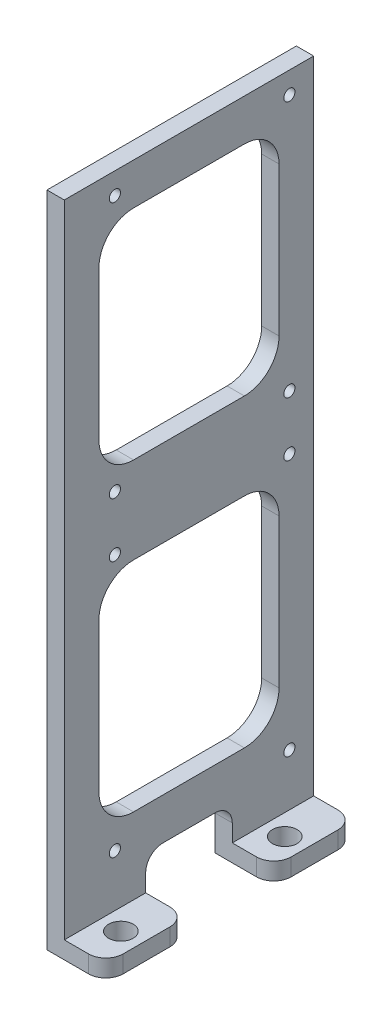
SolidWorks part; units mm, degrees
material "6061 Alloy"
ref_plane "Front Plane" through (0, 0, 0) normal (0, 0, 1) x (1, 0, 0)
ref_plane "Top Plane" through (0, 0, 0) normal (0, 1, 0) x (1, 0, 0)
ref_plane "Right Plane" through (0, 0, 0) normal (1, 0, 0) x (0, 0, -1)
sketch "Sketch1" plane through (0, 0, 0) normal (1, 0, 0) x (0, 0, -1)
  line L1 (-22.86, -60.325) -> (22.86, -60.325)
  line L2 (-22.86, -60.325) -> (-22.86, 60.325)
  line L3 (-22.86, 60.325) -> (22.86, 60.325)
  line L4 (22.86, -60.325) -> (22.86, 60.325)
  line L5 (-22.86, -60.325) -> (22.86, 60.325) construction
  line L6 (-22.86, 60.325) -> (22.86, -60.325) construction
  point P0 (0, 0)
  dimension "D1" = 120.65
  dimension "D2" = 45.72
extrude "Boss-Extrude1" add sketch "Sketch1" along normal blind 3.175
sketch "Sketch2" plane through (3.175, 0, 0) normal (1, 0, 0) x (0, 0, -1)
  line L0 (22.86, -60.325) -> (22.86, 60.325) construction
  line L1 (-22.86, -60.325) -> (22.86, -60.325)
  line L2 (-22.86, -60.325) -> (-22.86, -57.15)
  line L3 (-22.86, -57.15) -> (22.86, -57.15)
  line L4 (22.86, -60.325) -> (22.86, -57.15)
  dimension "D1" = 3.175
extrude "Boss-Extrude2" add sketch "Sketch2" along normal blind 7.62
sketch "Sketch3" plane through (0, -60.325, 0) normal (0, -1, 0) x (1, 0, 0)
  line L0 (10.795, 22.86) -> (10.795, -22.86) construction
  line L1 (0, -7.9375) -> (10.795, -7.9375)
  line L2 (0, -7.9375) -> (0, 7.9375)
  line L3 (0, 7.9375) -> (10.795, 7.9375)
  line L4 (10.795, -7.9375) -> (10.795, 7.9375)
  line L5 (0, -7.9375) -> (10.795, 7.9375) construction
  line L6 (0, 7.9375) -> (10.795, -7.9375) construction
  line L7 (0, 22.86) -> (0, -22.86) construction
  point P0 (5.3975, 0)
  dimension "D1" = 15.875
extrude "Cut-Extrude1" cut sketch "Sketch3" against normal blind 9.525
hole_wizard "M4 Clearance Hole1" positions "Sketch5" profile "Sketch4" hole size "M4" standard "Ansi Metric" end condition through all
sketch "Sketch5" plane through (0, -57.15, 0) normal (0, 1, 0) x (-1, 0, 0)
  line L7 (-6.985, 22.86) -> (-6.985, -22.86) construction
  line L8 (-10.795, 22.86) -> (-3.175, 22.86) construction
  line L9 (-10.795, -22.86) -> (-3.175, -22.86) construction
  line L11 (-22.011, 1.27) -> (-6.985, 16.296) construction
  line L13 (-22.011, 1.27) -> (-6.985, -13.756) construction
  circle A0 centre (-22.011, 1.27) radius 21.25
  point P0 (-6.985, -13.756)
  point P1 (-6.985, 16.296)
  dimension "D1" = 42.5
  dimension "D2" = 90
  dimension "D3" = 21.59
sketch "Sketch4" plane through (6.985, -57.15, -13.756) normal (1, 0, 0) x (0, 0, 1)
  line L0 (0, 0) -> (0, 3.175)
  line L1 (0, 3.175) -> (2.25, 3.175)
  line L2 (2.25, 3.175) -> (2.25, 0)
  line L5 (2.25, 0) -> (0, 0)
  line L11 (0, -6.35) -> (0, 107.95) construction
  dimension "Thru Hole Dia." = 4.5
  dimension "Thru Hole Depth" = 3.175
fillet "Fillet1" radius 3.175 2 edges at (1.5875, -50.8, 7.9375) (1.5875, -50.8, -7.9375)
fillet "Fillet2" radius 3.175 4 edges at (10.795, -58.7375, -22.86) (10.795, -58.7375, -7.9375) (10.795, -58.7375, 22.86) (10.795, -58.7375, 7.9375)
hole_wizard "M2.5x0.45 Tapped Hole1" positions "Sketch8" profile "Sketch9" tap size "M2.5x0.45" standard "Ansi Metric"
sketch "Sketch8" plane through (3.175, 0, 0) normal (1, 0, 0) x (0, 0, -1)
  line L1 (-13.585, 56.375) -> (18.415, 56.375) construction
  line L2 (-13.585, 56.375) -> (-13.585, -47.625) construction
  line L3 (-13.585, -47.625) -> (18.415, -47.625) construction
  line L4 (18.415, 56.375) -> (18.415, -47.625) construction
  line L5 (-13.585, 56.375) -> (18.415, -47.625) construction
  line L6 (-13.585, -47.625) -> (18.415, 56.375) construction
  line L7 (0, 60.325) -> (0, -50.8) construction
  line L8 (22.86, 60.325) -> (-22.86, 60.325) construction
  line L9 (-4.7625, -50.8) -> (4.7625, -50.8) construction
  line L10 (22.86, -57.15) -> (22.86, 60.325) construction
  point P174 (-13.585, -47.625)
  point P176 (18.415, -47.625)
  point P178 (18.415, -0.625)
  point P180 (-13.585, -0.625)
  point P182 (-13.585, 9.375)
  point P184 (18.415, 9.375)
  point P186 (18.415, 56.375)
  point P188 (-13.585, 56.375)
  dimension "D1" = 32
  dimension "D2" = 47
  dimension "D3" = 10
  dimension "D4" = 47
  dimension "D5" = 3.175
  dimension "D6" = 4.445
sketch "Sketch9" plane through (3.175, -47.625, 13.585) normal (0, 1, 0) x (0, 0, -1)
  line L0 (0, 0) -> (0, 6.9659)
  line L1 (0, 6.9659) -> (1.025, 6.35)
  line L2 (1.025, 6.35) -> (1.025, 0)
  line L5 (1.025, 0) -> (0, 0)
  line L10 (0, 6.9659) -> (-1.025, 6.35) construction
  line L11 (0, -6.35) -> (0, 107.95) construction
  dimension "Tap Drill Dia." = 2.05
  dimension "Tap Drill Depth" = 6.35
  dimension "Drill Angle" = 118
sketch "Sketch10" plane through (3.175, 0, 0) normal (1, 0, 0) x (0, 0, -1)
  line L0 (-22.86, 60.325) -> (-22.86, -57.15) construction
  line L1 (-16.51, 52.705) -> (16.51, 52.705)
  line L2 (-16.51, 52.705) -> (-16.51, 12.7)
  line L3 (-16.51, 12.7) -> (16.51, 12.7)
  line L4 (16.51, 52.705) -> (16.51, 12.7)
  line L5 (-16.51, 52.705) -> (16.51, 12.7) construction
  line L6 (-16.51, 12.7) -> (16.51, 52.705) construction
  line L13 (-16.51, -43.18) -> (16.51, -43.18)
  line L14 (-16.51, -43.18) -> (-16.51, -3.175)
  line L15 (-16.51, -3.175) -> (16.51, -3.175)
  line L16 (16.51, -43.18) -> (16.51, -3.175)
  line L17 (-16.51, -43.18) -> (16.51, -3.175) construction
  line L18 (-16.51, -3.175) -> (16.51, -43.18) construction
  line L19 (22.86, -57.15) -> (22.86, 60.325) construction
  line L20 (22.86, 60.325) -> (-22.86, 60.325) construction
  line L21 (-4.7625, -50.8) -> (4.7625, -50.8) construction
  point P0 (0, 32.7025)
  point P10 (0, -23.1775)
  dimension "D1" = 6.35
  dimension "D2" = 6.35
  dimension "D3" = 7.62
  dimension "D4" = 7.62
  dimension "D5" = 12.7
  dimension "D6" = 3.175
extrude "Cut-Extrude2" cut sketch "Sketch10" against normal through all
fillet "Fillet3" radius 6.35 8 edges at (1.5875, -43.18, -16.51) (1.5875, -43.18, 16.51) (1.5875, -3.175, 16.51) (1.5875, -3.175, -16.51) (1.5875, 52.705, -16.51) (1.5875, 52.705, 16.51) (1.5875, 12.7, -16.51) (1.5875, 12.7, 16.51)
